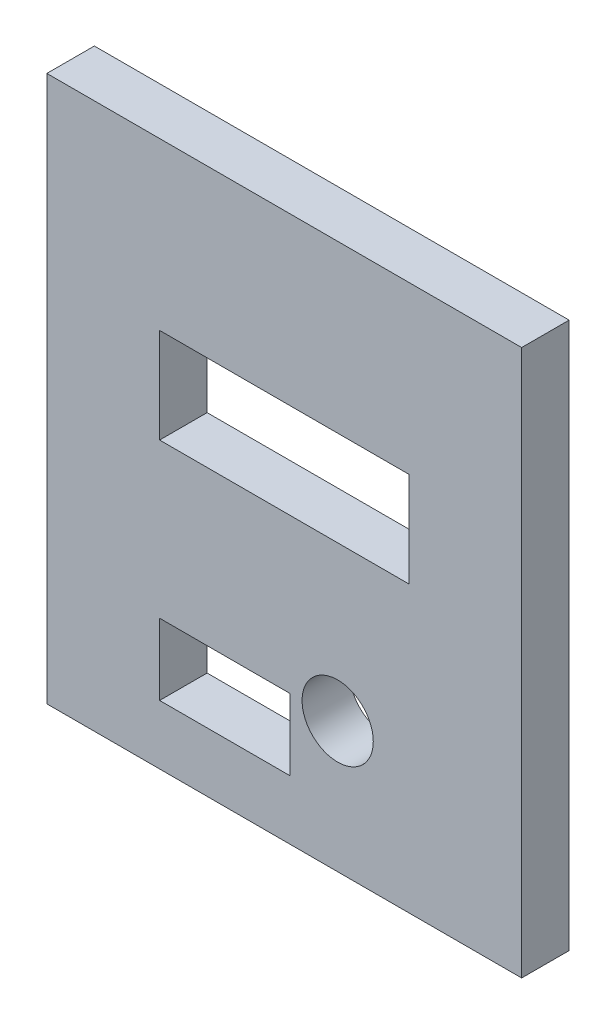
SolidWorks part; units mm, degrees
material "Perspex (TM) GS Acrylic Cast Sheet"
ref_plane "Front Plane" through (0, 0, 0) normal (0, 0, 1) x (1, 0, 0)
ref_plane "Top Plane" through (0, 0, 0) normal (0, 1, 0) x (1, 0, 0)
ref_plane "Right Plane" through (0, 0, 0) normal (1, 0, 0) x (0, 0, -1)
sketch "Sketch1" plane through (0, 0, 0) normal (0, 0, 1) x (1, 0, 0)
  line L1 (10, -11.5) -> (-10, -11.5)
  line L2 (10, -11.5) -> (10, 11.5)
  line L3 (10, 11.5) -> (-10, 11.5)
  line L4 (-10, -11.5) -> (-10, 11.5)
  line L5 (10, -11.5) -> (-10, 11.5) construction
  line L6 (10, 11.5) -> (-10, -11.5) construction
  point P0 (0, 0)
  dimension "D1" = 20
  dimension "D2" = 23
extrude "Boss-Extrude1" add sketch "Sketch1" along normal blind 2
sketch "Sketch2" plane through (0, 0, 2) normal (0, 0, 1) x (1, 0, 0)
  line L0 (0, 0) -> (0, 11.5) construction
  line L1 (10, 11.5) -> (-10, 11.5) construction
  line L2 (-10, -11.5) -> (10, -11.5) construction
  line L3 (5.25, -9) -> (-5.25, -9)
  line L4 (5.25, -9) -> (5.25, 4.5)
  line L5 (5.25, 4.5) -> (-5.25, 4.5)
  line L6 (-5.25, -9) -> (-5.25, 4.5)
  line L7 (5.25, -9) -> (-5.25, 4.5) construction
  line L8 (5.25, 4.5) -> (-5.25, -9) construction
  line L10 (5.25, 0.5) -> (-5.25, 0.5)
  line L11 (5.25, 0.5) -> (5.25, 4.5)
  line L12 (5.25, 4.5) -> (-5.25, 4.5)
  line L13 (-5.25, 0.5) -> (-5.25, 4.5)
  line L14 (5.25, 0.5) -> (-5.25, 4.5) construction
  line L15 (5.25, 4.5) -> (-5.25, 0.5) construction
  line L16 (0.25, -9) -> (-5.25, -9)
  line L17 (0.25, -9) -> (0.25, -6)
  line L18 (0.25, -6) -> (-5.25, -6)
  line L19 (-5.25, -9) -> (-5.25, -6)
  line L20 (0.25, -9) -> (-5.25, -6) construction
  line L21 (0.25, -6) -> (-5.25, -9) construction
  circle A0 centre (2.25, -6) radius 1.5
  point P5 (0, -2.25)
  point P12 (0, 2.5)
  point P13 (-2.5, -7.5)
  dimension "D4" = 3
  dimension "D1" = 2.5
  dimension "D2" = 13.5
  dimension "D3" = 10.5
  dimension "D5" = 3
  dimension "D6" = 3
  dimension "D7" = 5.5
  dimension "D8" = 2.5
  dimension "D9" = 3
  dimension "D10" = 4
extrude "Cut-Extrude1" cut sketch "Sketch2" against normal blind 10 contours L10 L4 L5 L6 | L17 L18 L6 L16 | A0
